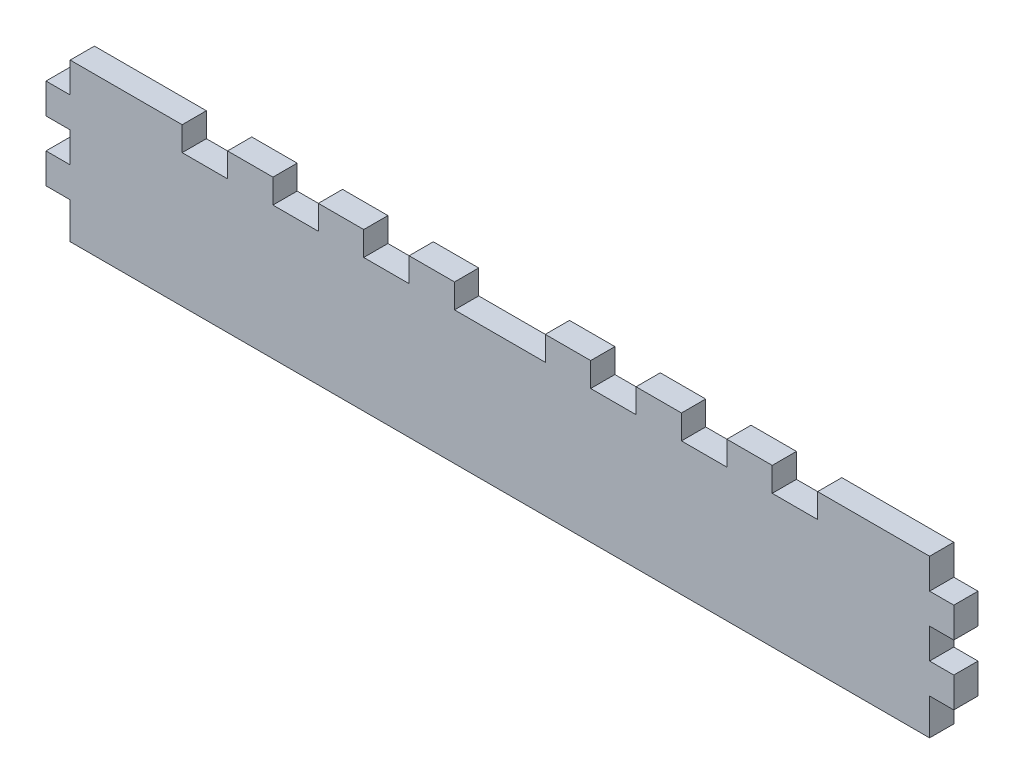
SolidWorks part; units mm, degrees
ref_plane "Plan de face" through (0, 0, 0) normal (0, 0, 1) x (1, 0, 0)
ref_plane "Plan de dessus" through (0, 0, 0) normal (0, 1, 0) x (1, 0, 0)
ref_plane "Plan de droite" through (0, 0, 0) normal (1, 0, 0) x (0, 0, -1)
sketch "Esquisse1" plane through (0, 0, 0) normal (0, 0, 1) x (1, 0, 0)
  line L1 (-150, -26) -> (150, -26)
  line L2 (-150, -26) -> (-150, 26)
  line L3 (-150, 26) -> (150, 26)
  line L4 (150, -26) -> (150, 26)
  line L5 (-150, -26) -> (150, 26) construction
  line L6 (-150, 26) -> (150, -26) construction
  point P0 (0, 0)
  dimension "D1" = 300
  dimension "D2" = 52
extrude "Boss.-Extru.1" add sketch "Esquisse1" along normal blind 8
sketch "Esquisse2" plane through (0, 0, 0) normal (0, 0, 1) x (1, 0, 0)
  line L0 (-150, 6) -> (-150, -4)
  line L1 (-150, 26) -> (-142, 26)
  line L2 (-150, 26) -> (-150, 16)
  line L3 (-150, 16) -> (-142, 16)
  line L4 (-142, 26) -> (-142, 16)
  line L5 (-150, 6) -> (-142, 6)
  line L6 (-142, 6) -> (-142, -4)
  line L7 (-150, -4) -> (-142, -4)
  line L8 (-150, -14) -> (-150, -24)
  line L9 (-150, -14) -> (-142, -14)
  line L10 (-142, -14) -> (-142, -24)
  line L11 (-150, -24) -> (-142, -24)
  dimension "D1" = 10
  dimension "D2" = 8
  dimension "D3" = 3
extrude "Enlèv. mat.-Extru.1" cut sketch "Esquisse2" along normal through all
sketch "Esquisse3" plane through (0, 0, 0) normal (0, 0, 1) x (1, 0, 0)
  line L1 (-150, -26) -> (-142, -26)
  line L2 (-150, -26) -> (-150, -24)
  line L3 (-150, -24) -> (-142, -24)
  line L4 (-142, -26) -> (-142, -24)
extrude "Enlèv. mat.-Extru.2" cut sketch "Esquisse3" along normal through all
mirror "Symétrie1" about plane through (0, 0, 0) normal (1, 0, 0) of "Enlèv. mat.-Extru.2", "Enlèv. mat.-Extru.1"
sketch "Esquisse4" plane through (0, 0, 0) normal (0, 0, 1) x (1, 0, 0)
  line L0 (0, 0) -> (0, 19.8541) construction
  line L1 (142, 26) -> (-142, 26) construction
  line L2 (0, 26) -> (-15, 26)
  line L4 (0, 18) -> (-15, 18)
  line L5 (-15, 26) -> (-15, 18)
  line L6 (-30, 26) -> (-30, 18)
  line L7 (-30, 26) -> (-45, 26)
  line L8 (-45, 26) -> (-45, 18)
  line L9 (-30, 18) -> (-45, 18)
  line L10 (-60, 26) -> (-60, 18)
  line L11 (-60, 26) -> (-75, 26)
  line L12 (-75, 26) -> (-75, 18)
  line L13 (-60, 18) -> (-75, 18)
  line L14 (-90, 26) -> (-90, 18)
  line L15 (-90, 26) -> (-105, 26)
  line L16 (-105, 26) -> (-105, 18)
  line L17 (-90, 18) -> (-105, 18)
  line L18 (30, 26) -> (45, 26)
  line L19 (45, 26) -> (45, 18)
  line L20 (30, 18) -> (45, 18)
  line L21 (30, 26) -> (30, 18)
  line L22 (60, 26) -> (75, 26)
  line L23 (75, 26) -> (75, 18)
  line L24 (60, 18) -> (75, 18)
  line L25 (60, 26) -> (60, 18)
  line L26 (90, 26) -> (105, 26)
  line L27 (105, 26) -> (105, 18)
  line L28 (90, 18) -> (105, 18)
  line L29 (90, 26) -> (90, 18)
  line L31 (0, 26) -> (15, 26)
  line L32 (0, 19.8541) -> (0, 18)
  line L33 (0, 18) -> (15, 18)
  line L34 (15, 26) -> (15, 18)
  dimension "D1" = 15
  dimension "D2" = 8
  dimension "D4" = 15
  dimension "D3" = 4
extrude "Enlèv. mat.-Extru.3" cut sketch "Esquisse4" along normal blind 10 contours L17 L14 L15 L16 | L9 L6 L7 L8 | L18 L21 L20 L19 | L22 L25 L24 L23 | L26 L29 L28 L27 | L12 L13 L10 L11 | L33 L34 L31 L2 L5 L4
